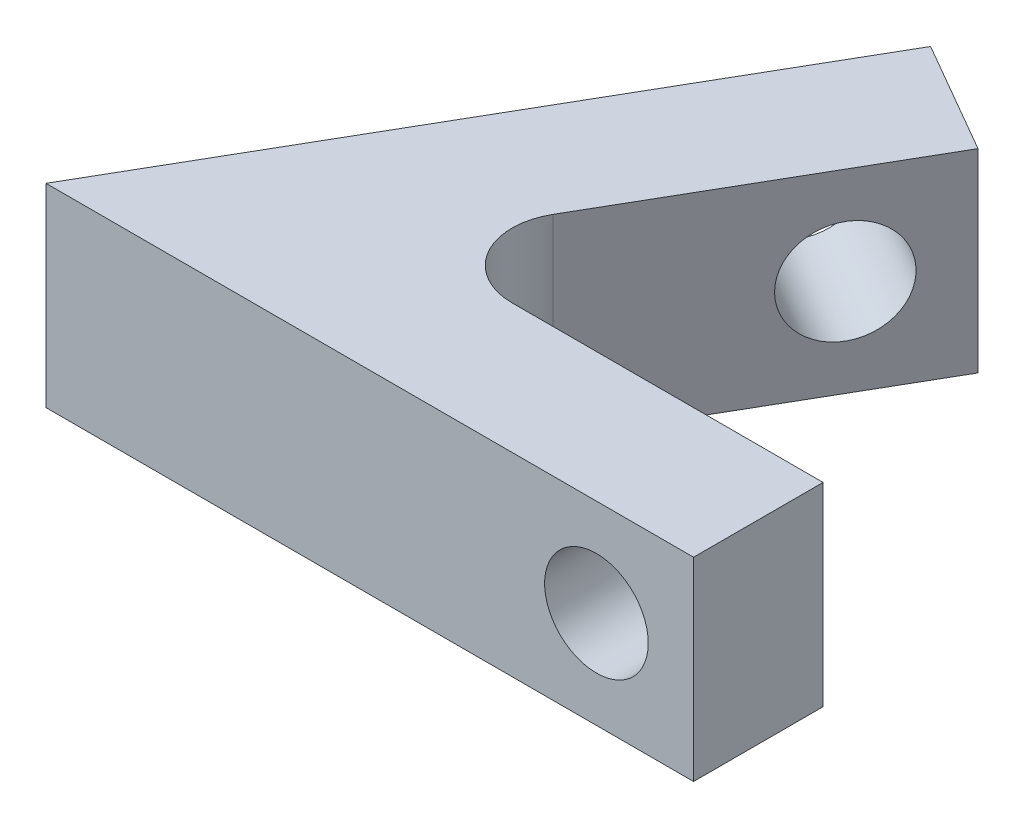
SolidWorks part; units mm, degrees
ref_plane "前视基准面" through (0, 0, 0) normal (0, 0, 1) x (1, 0, 0)
ref_plane "上视基准面" through (0, 0, 0) normal (0, 1, 0) x (1, 0, 0)
ref_plane "右视基准面" through (0, 0, 0) normal (1, 0, 0) x (0, 0, -1)
sketch "草图2" plane through (0, 0, 0) normal (0, 1, 0) x (1, 0, 0)
  line L0 (0, 0) -> (13.0718, 0)
  line L1 (13.0718, 0) -> (13.0718, -4)
  line L2 (13.0718, -4) -> (-6.9282, -4)
  line L3 (-6.9282, -4) -> (3.0718, 13.3205)
  line L4 (3.0718, 13.3205) -> (6.5359, 11.3205)
  line L5 (6.5359, 11.3205) -> (0, 0)
  dimension "D1" = 4
  dimension "D2" = 4
  dimension "D3" = 60
  dimension "D4" = 20
  dimension "D5" = 20
extrude "凸台-拉伸1" add sketch "草图2" along normal blind 6
sketch "草图3" plane through (0, 0, 4) normal (0, 0, 1) x (1, 0, 0)
  line L0 (-6.9282, 3) -> (13.0718, 3) construction
  line L1 (-6.9282, 6) -> (-6.9282, 0) construction
  line L2 (13.0718, 6) -> (13.0718, 0) construction
  circle A0 centre (10.0718, 3) radius 1.6
  dimension "D1" = 3.2
  dimension "D2" = 3
extrude "切除-拉伸1" cut sketch "草图3" against normal up to next
ref_plane "基准面1" through (0, 0, 0) normal (0.5, 0, 0.866) x (0.866, 0, -0.5)
mirror "镜向1" about plane through (0, 0, 0) normal (0.5, 0, 0.866) of "切除-拉伸1"
fillet "圆角1" radius 2 1 edges at (0, 3, 0)
